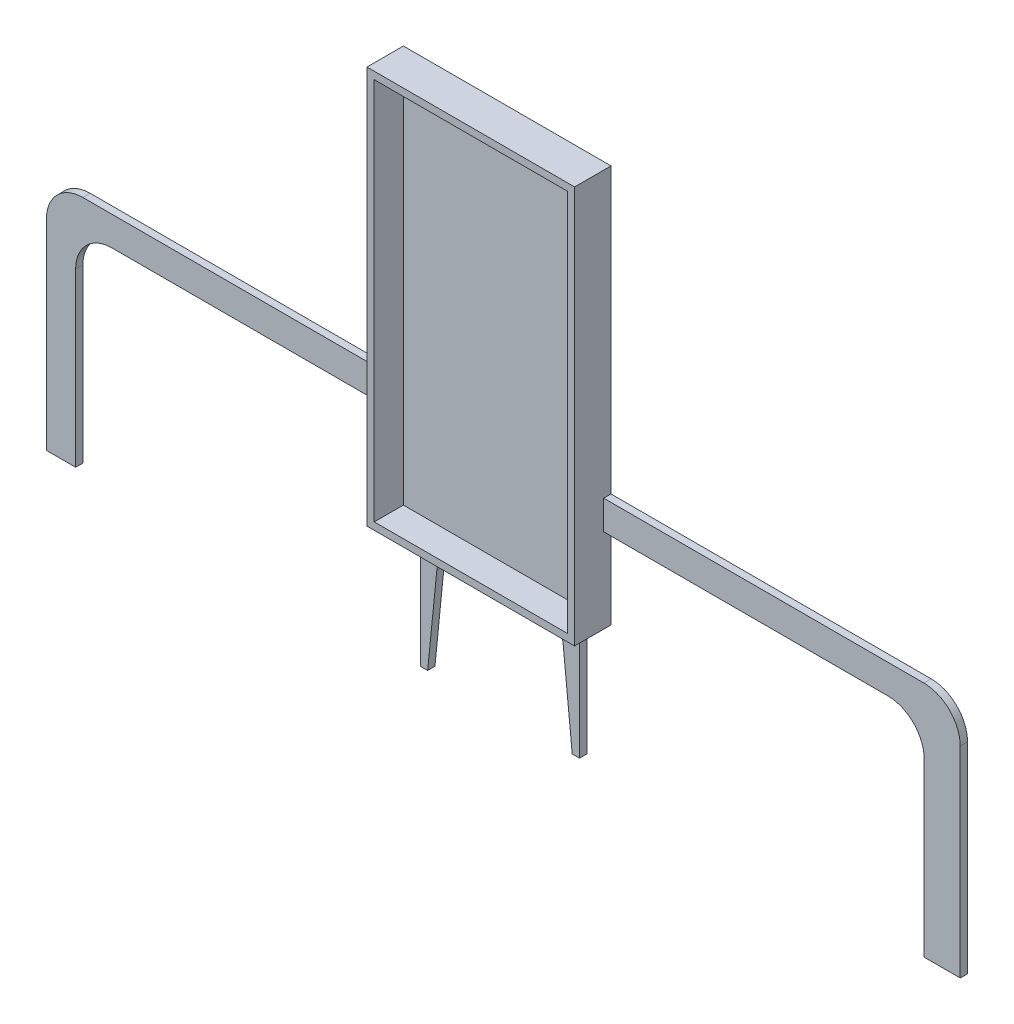
SolidWorks part; units mm, degrees
ref_plane "Plan de face" through (0, 0, 0) normal (0, 0, 1) x (1, 0, 0)
ref_plane "Plan de dessus" through (0, 0, 0) normal (0, 1, 0) x (1, 0, 0)
ref_plane "Plan de droite" through (0, 0, 0) normal (1, 0, 0) x (0, 0, -1)
sketch "Esquisse1" plane through (0, 0, 0) normal (0, 0, 1) x (1, 0, 0)
  line L0 (0, 0) -> (0, 27.5696)
  line L1 (5, 32.5696) -> (120.4159, 32.5696)
  line L2 (125.4159, 27.5696) -> (125.4159, 0)
  line L3 (0, 0) -> (4, 0)
  line L4 (4, 0) -> (4, 23.5696)
  line L5 (9, 28.5696) -> (115.4701, 28.5696)
  line L6 (120.4701, 23.5696) -> (120.4701, 0)
  line L7 (120.4701, 0) -> (125.4159, 0)
  line L8 (0, 28.5696) -> (4, 28.5696) construction
  line L9 (40.9314, 32.5696) -> (40.9314, 28.5696) construction
  line L10 (4, 0) -> (52.3195, 0) construction
  line L11 (52.3195, 0) -> (52.3195, 28.5696) construction
  line L12 (120.4701, 0) -> (72.1589, 0) construction
  line L13 (72.1589, 0) -> (72.1589, 28.5696) construction
  line L14 (52.3195, 0) -> (72.1589, 0) construction
  line L15 (62.2392, 0) -> (62.2392, 17) construction
  line L16 (52.3195, 17) -> (72.1589, 17)
  line L17 (72.1589, 17) -> (72.1589, 28.5696)
  line L18 (72.1589, 28.5696) -> (52.3195, 28.5696)
  line L19 (52.3195, 28.5696) -> (52.3195, 17)
  line L20 (57.4149, 0) -> (57.4149, 17) construction
  line L21 (52.3195, 17) -> (57.4149, 17) construction
  line L22 (52.3195, 0) -> (53.5679, 12.497)
  line L23 (72.1589, 0) -> (72.1589, 17)
  line L24 (58.5431, 17) -> (65.9353, 17)
  line L25 (67.0635, 0) -> (67.0635, 17) construction
  line L26 (57.4149, 17) -> (62.2392, 17) construction
  line L27 (72.1589, 0) -> (70.9105, 12.497)
  line L32 (62.235, 28.5696) -> (62.235, 71.5696) construction
  line L36 (72.1589, 0) -> (72.1589, 17)
  line L42 (72.1589, 17) -> (52.3195, 17)
  line L43 (62.235, 71.5696) -> (47.985, 71.5696) construction
  line L44 (62.235, 71.5696) -> (76.485, 71.5696) construction
  line L45 (76.485, 71.5696) -> (76.485, 28.5696) construction
  line L46 (47.985, 71.5696) -> (47.985, 28.5696) construction
  line L47 (53.5679, 12.497) -> (70.9105, 12.497) construction
  line L48 (52.3195, 0) -> (52.3195, 17)
  line L50 (52.3195, 28.5696) -> (51.3195, 28.5696)
  line L51 (72.1589, 28.5696) -> (73.1589, 28.5696)
  line L52 (72.1589, 28.5696) -> (72.1589, 0)
  line L53 (72.1589, 0) -> (73.1589, 0)
  line L54 (73.1589, 28.5696) -> (73.1589, 0)
  line L55 (52.3195, 28.5696) -> (52.3195, 0)
  line L56 (52.3195, 0) -> (51.3195, 0)
  line L57 (51.3195, 28.5696) -> (51.3195, 0)
  line L61 (47.985, 28.5696) -> (47.985, 17) construction
  line L62 (47.985, 17) -> (76.485, 17) construction
  line L63 (76.485, 17) -> (76.485, 28.5696) construction
  line L69 (47.985, 71.5696) -> (76.485, 71.5696)
  line L70 (47.985, 71.5696) -> (47.985, 17)
  line L71 (47.985, 17) -> (76.485, 17)
  line L72 (76.485, 71.5696) -> (76.485, 17)
  arc A0 (4, 23.5696) -> (9, 28.5696) centre (9, 23.5696) cw
  arc A1 (0, 27.5696) -> (5, 32.5696) centre (5, 27.5696) cw
  arc A2 (115.4701, 28.5696) -> (120.4701, 23.5696) centre (115.4701, 23.5696) cw
  arc A3 (120.4159, 32.5696) -> (125.4159, 27.5696) centre (120.4159, 27.5696) cw
  arc A4 (53.5679, 12.497) -> (58.5431, 17) centre (58.5431, 12) cw
  arc A5 (70.9105, 12.497) -> (65.9353, 17) centre (65.9353, 12) ccw
  point P33 (52.3195, 0)
  point P35 (62.2392, 17)
  point P37 (62.2392, 17)
  dimension "D1" = 5
  dimension "D2" = 5
  dimension "D3" = 5
extrude "Boss.-Extru.1" add sketch "Esquisse1" along normal blind 1
sketch "Esquisse2" plane through (0, 0, 1) normal (0, 0, 1) x (1, 0, 0)
  line L0 (75.485, 70.5696) -> (75.485, 71.5696) construction
  line L2 (76.485, 70.5696) -> (75.485, 70.5696) construction
  line L4 (76.485, 71.5696) -> (76.485, 32.5696) construction
  line L5 (47.985, 71.5696) -> (76.485, 71.5696) construction
  line L6 (47.985, 17) -> (51.3195, 17) construction
  line L7 (47.985, 18) -> (48.985, 18) construction
  line L8 (47.985, 28.5696) -> (47.985, 17) construction
  line L9 (48.985, 18) -> (48.985, 17) construction
  line L10 (47.985, 71.5696) -> (76.485, 71.5696)
  line L15 (76.485, 71.5696) -> (76.485, 17)
  line L16 (76.485, 17) -> (47.985, 17)
  line L17 (47.985, 17) -> (47.985, 71.5696)
  line L18 (75.485, 17) -> (75.485, 18) construction
  line L19 (75.485, 18) -> (76.485, 18) construction
  line L20 (48.985, 71.5696) -> (48.985, 70.5696) construction
  line L21 (48.985, 70.5696) -> (47.985, 70.5696) construction
  line L22 (48.985, 70.5696) -> (75.485, 70.5696)
  line L23 (75.485, 70.5696) -> (75.485, 18)
  line L24 (75.485, 18) -> (48.985, 18)
  line L25 (48.985, 18) -> (48.985, 70.5696)
extrude "Boss.-Extru.2" add sketch "Esquisse2" along normal blind 4
